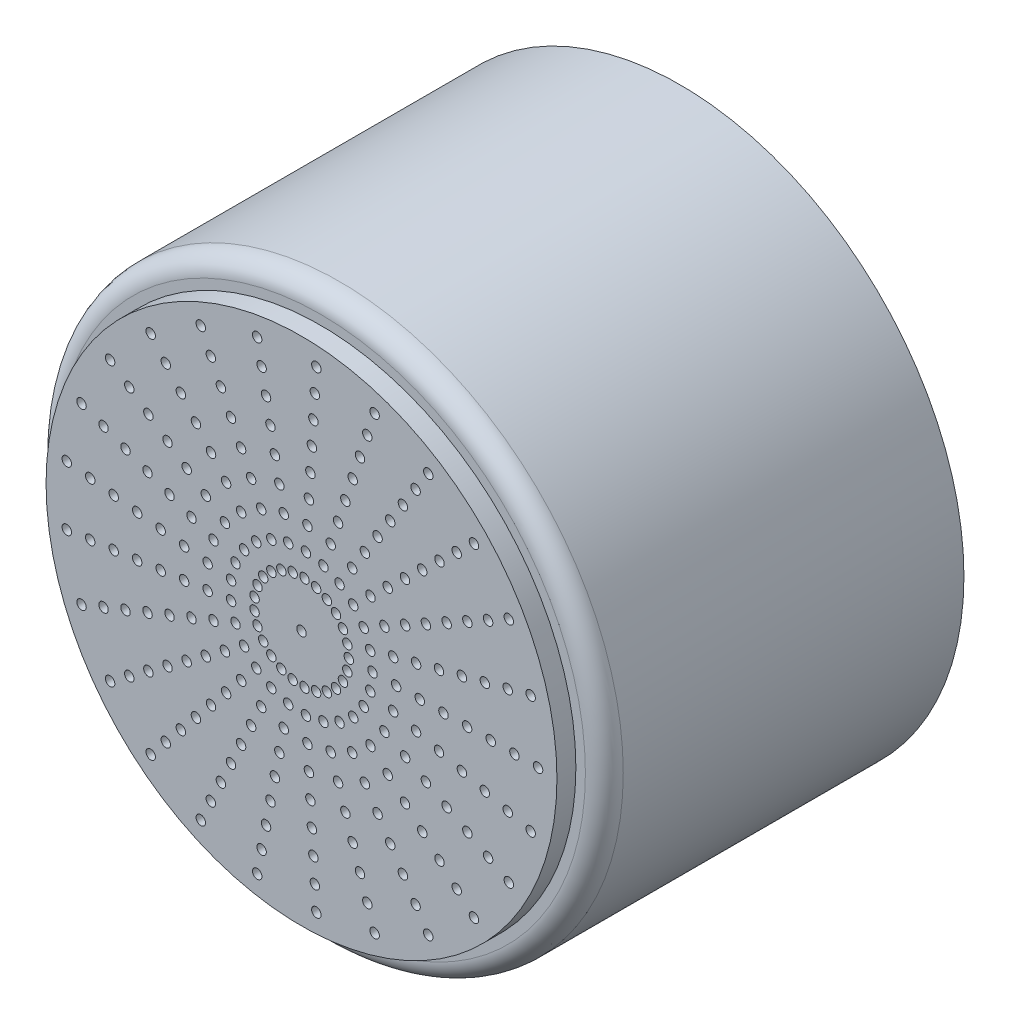
SolidWorks part; units mm, degrees
ref_plane "Ebene vorne" through (0, 0, 0) normal (0, 0, 1) x (1, 0, 0)
ref_plane "Ebene oben" through (0, 0, 0) normal (0, 1, 0) x (1, 0, 0)
ref_plane "Ebene rechts" through (0, 0, 0) normal (1, 0, 0) x (0, 0, -1)
sketch "Skizze1" plane through (0, 0, 0) normal (0, 0, 1) x (1, 0, 0)
  circle A0 centre (0, 0) radius 3
extrude "Aufsatz-Linear austragen1" add sketch "Skizze1" along normal blind 3.8
fillet "Verrundung1" radius 0.2 1 edges at (3, 0, 3.8)
sketch "Skizze2" plane through (0, 0, 3.8) normal (0, 0, 1) x (1, 0, 0)
  circle A0 centre (0, 0) radius 2.6993
extrude "Aufsatz-Linear austragen2" add sketch "Skizze2" along normal blind 0.2
sketch "Skizze3" plane through (0, 0, 4) normal (0, 0, 1) x (1, 0, 0)
  circle A0 centre (0, 0) radius 0.05
  circle A2 centre (0.5, 0) radius 0.05
  circle A3 centre (0.75, 0) radius 0.05
  circle A4 centre (1, 0) radius 0.05
  circle A5 centre (1.25, 0) radius 0.05
  circle A6 centre (1.5, 0) radius 0.05
  circle A7 centre (1.75, 0) radius 0.05
  circle A8 centre (2, 0) radius 0.05
  circle A9 centre (2.25, 0) radius 0.05
  circle A10 centre (2.5, 0) radius 0.05
  circle A11 centre (0, 0) radius 0.05
  circle A13 centre (0.4843, -0.1243) radius 0.05
  circle A14 centre (0.7264, -0.1865) radius 0.05
  circle A15 centre (0.9686, -0.2487) radius 0.05
  circle A16 centre (1.2107, -0.3109) radius 0.05
  circle A17 centre (1.4529, -0.373) radius 0.05
  circle A18 centre (1.695, -0.4352) radius 0.05
  circle A19 centre (1.9372, -0.4974) radius 0.05
  circle A20 centre (2.1793, -0.5596) radius 0.05
  circle A21 centre (2.4215, -0.6217) radius 0.05
  circle A22 centre (0, 0) radius 0.05
  circle A24 centre (0.4382, -0.2409) radius 0.05
  circle A25 centre (0.6572, -0.3613) radius 0.05
  circle A26 centre (0.8763, -0.4818) radius 0.05
  circle A27 centre (1.0954, -0.6022) radius 0.05
  circle A28 centre (1.3145, -0.7226) radius 0.05
  circle A29 centre (1.5335, -0.8431) radius 0.05
  circle A30 centre (1.7526, -0.9635) radius 0.05
  circle A31 centre (1.9717, -1.0839) radius 0.05
  circle A32 centre (2.1908, -1.2044) radius 0.05
  circle A33 centre (0, 0) radius 0.05
  circle A35 centre (0.3645, -0.3423) radius 0.05
  circle A36 centre (0.5467, -0.5134) radius 0.05
  circle A37 centre (0.729, -0.6845) radius 0.05
  circle A38 centre (0.9112, -0.8557) radius 0.05
  circle A39 centre (1.0935, -1.0268) radius 0.05
  circle A40 centre (1.2757, -1.198) radius 0.05
  circle A41 centre (1.4579, -1.3691) radius 0.05
  circle A42 centre (1.6402, -1.5402) radius 0.05
  circle A43 centre (1.8224, -1.7114) radius 0.05
  circle A44 centre (0, 0) radius 0.05
  circle A46 centre (0.2679, -0.4222) radius 0.05
  circle A47 centre (0.4019, -0.6332) radius 0.05
  circle A48 centre (0.5358, -0.8443) radius 0.05
  circle A49 centre (0.6698, -1.0554) radius 0.05
  circle A50 centre (0.8037, -1.2665) radius 0.05
  circle A51 centre (0.9377, -1.4776) radius 0.05
  circle A52 centre (1.0717, -1.6887) radius 0.05
  circle A53 centre (1.2056, -1.8997) radius 0.05
  circle A54 centre (1.3396, -2.1108) radius 0.05
  circle A55 centre (0, 0) radius 0.05
  circle A57 centre (0.1545, -0.4755) radius 0.05
  circle A58 centre (0.2318, -0.7133) radius 0.05
  circle A59 centre (0.309, -0.9511) radius 0.05
  circle A60 centre (0.3863, -1.1888) radius 0.05
  circle A61 centre (0.4635, -1.4266) radius 0.05
  circle A62 centre (0.5408, -1.6643) radius 0.05
  circle A63 centre (0.618, -1.9021) radius 0.05
  circle A64 centre (0.6953, -2.1399) radius 0.05
  circle A65 centre (0.7725, -2.3776) radius 0.05
  circle A66 centre (0, 0) radius 0.05
  circle A68 centre (0.0314, -0.499) radius 0.05
  circle A69 centre (0.0471, -0.7485) radius 0.05
  circle A70 centre (0.0628, -0.998) radius 0.05
  circle A71 centre (0.0785, -1.2475) radius 0.05
  circle A72 centre (0.0942, -1.497) radius 0.05
  circle A73 centre (0.1099, -1.7465) radius 0.05
  circle A74 centre (0.1256, -1.9961) radius 0.05
  circle A75 centre (0.1413, -2.2456) radius 0.05
  circle A76 centre (0.157, -2.4951) radius 0.05
  circle A77 centre (0, 0) radius 0.05
  circle A79 centre (-0.0937, -0.4911) radius 0.05
  circle A80 centre (-0.1405, -0.7367) radius 0.05
  circle A81 centre (-0.1874, -0.9823) radius 0.05
  circle A82 centre (-0.2342, -1.2279) radius 0.05
  circle A83 centre (-0.2811, -1.4734) radius 0.05
  circle A84 centre (-0.3279, -1.719) radius 0.05
  circle A85 centre (-0.3748, -1.9646) radius 0.05
  circle A86 centre (-0.4216, -2.2101) radius 0.05
  circle A87 centre (-0.4685, -2.4557) radius 0.05
  circle A88 centre (0, 0) radius 0.05
  circle A90 centre (-0.2129, -0.4524) radius 0.05
  circle A91 centre (-0.3193, -0.6786) radius 0.05
  circle A92 centre (-0.4258, -0.9048) radius 0.05
  circle A93 centre (-0.5322, -1.131) radius 0.05
  circle A94 centre (-0.6387, -1.3572) radius 0.05
  circle A95 centre (-0.7451, -1.5834) radius 0.05
  circle A96 centre (-0.8516, -1.8097) radius 0.05
  circle A97 centre (-0.958, -2.0359) radius 0.05
  circle A98 centre (-1.0644, -2.2621) radius 0.05
  circle A99 centre (0, 0) radius 0.05
  circle A101 centre (-0.3187, -0.3853) radius 0.05
  circle A102 centre (-0.4781, -0.5779) radius 0.05
  circle A103 centre (-0.6374, -0.7705) radius 0.05
  circle A104 centre (-0.7968, -0.9631) radius 0.05
  circle A105 centre (-0.9561, -1.1558) radius 0.05
  circle A106 centre (-1.1155, -1.3484) radius 0.05
  circle A107 centre (-1.2748, -1.541) radius 0.05
  circle A108 centre (-1.4342, -1.7337) radius 0.05
  circle A109 centre (-1.5936, -1.9263) radius 0.05
  circle A110 centre (0, 0) radius 0.05
  circle A112 centre (-0.4045, -0.2939) radius 0.05
  circle A113 centre (-0.6068, -0.4408) radius 0.05
  circle A114 centre (-0.809, -0.5878) radius 0.05
  circle A115 centre (-1.0113, -0.7347) radius 0.05
  circle A116 centre (-1.2135, -0.8817) radius 0.05
  circle A117 centre (-1.4158, -1.0286) radius 0.05
  circle A118 centre (-1.618, -1.1756) radius 0.05
  circle A119 centre (-1.8203, -1.3225) radius 0.05
  circle A120 centre (-2.0225, -1.4695) radius 0.05
  circle A121 centre (0, 0) radius 0.05
  circle A123 centre (-0.4649, -0.1841) radius 0.05
  circle A124 centre (-0.6973, -0.2761) radius 0.05
  circle A125 centre (-0.9298, -0.3681) radius 0.05
  circle A126 centre (-1.1622, -0.4602) radius 0.05
  circle A127 centre (-1.3947, -0.5522) radius 0.05
  circle A128 centre (-1.6271, -0.6442) radius 0.05
  circle A129 centre (-1.8596, -0.7362) radius 0.05
  circle A130 centre (-2.092, -0.8283) radius 0.05
  circle A131 centre (-2.3244, -0.9203) radius 0.05
  circle A132 centre (0, 0) radius 0.05
  circle A134 centre (-0.4961, -0.0627) radius 0.05
  circle A135 centre (-0.7441, -0.094) radius 0.05
  circle A136 centre (-0.9921, -0.1253) radius 0.05
  circle A137 centre (-1.2401, -0.1567) radius 0.05
  circle A138 centre (-1.4882, -0.188) radius 0.05
  circle A139 centre (-1.7362, -0.2193) radius 0.05
  circle A140 centre (-1.9842, -0.2507) radius 0.05
  circle A141 centre (-2.2323, -0.282) radius 0.05
  circle A142 centre (-2.4803, -0.3133) radius 0.05
  circle A143 centre (0, 0) radius 0.05
  circle A145 centre (-0.4961, 0.0627) radius 0.05
  circle A146 centre (-0.7441, 0.094) radius 0.05
  circle A147 centre (-0.9921, 0.1253) radius 0.05
  circle A148 centre (-1.2401, 0.1567) radius 0.05
  circle A149 centre (-1.4882, 0.188) radius 0.05
  circle A150 centre (-1.7362, 0.2193) radius 0.05
  circle A151 centre (-1.9842, 0.2507) radius 0.05
  circle A152 centre (-2.2323, 0.282) radius 0.05
  circle A153 centre (-2.4803, 0.3133) radius 0.05
  circle A154 centre (0, 0) radius 0.05
  circle A156 centre (-0.4649, 0.1841) radius 0.05
  circle A157 centre (-0.6973, 0.2761) radius 0.05
  circle A158 centre (-0.9298, 0.3681) radius 0.05
  circle A159 centre (-1.1622, 0.4602) radius 0.05
  circle A160 centre (-1.3947, 0.5522) radius 0.05
  circle A161 centre (-1.6271, 0.6442) radius 0.05
  circle A162 centre (-1.8596, 0.7362) radius 0.05
  circle A163 centre (-2.092, 0.8283) radius 0.05
  circle A164 centre (-2.3244, 0.9203) radius 0.05
  circle A165 centre (0, 0) radius 0.05
  circle A167 centre (-0.4045, 0.2939) radius 0.05
  circle A168 centre (-0.6068, 0.4408) radius 0.05
  circle A169 centre (-0.809, 0.5878) radius 0.05
  circle A170 centre (-1.0113, 0.7347) radius 0.05
  circle A171 centre (-1.2135, 0.8817) radius 0.05
  circle A172 centre (-1.4158, 1.0286) radius 0.05
  circle A173 centre (-1.618, 1.1756) radius 0.05
  circle A174 centre (-1.8203, 1.3225) radius 0.05
  circle A175 centre (-2.0225, 1.4695) radius 0.05
  circle A176 centre (0, 0) radius 0.05
  circle A178 centre (-0.3187, 0.3853) radius 0.05
  circle A179 centre (-0.4781, 0.5779) radius 0.05
  circle A180 centre (-0.6374, 0.7705) radius 0.05
  circle A181 centre (-0.7968, 0.9631) radius 0.05
  circle A182 centre (-0.9561, 1.1558) radius 0.05
  circle A183 centre (-1.1155, 1.3484) radius 0.05
  circle A184 centre (-1.2748, 1.541) radius 0.05
  circle A185 centre (-1.4342, 1.7337) radius 0.05
  circle A186 centre (-1.5936, 1.9263) radius 0.05
  circle A187 centre (0, 0) radius 0.05
  circle A189 centre (-0.2129, 0.4524) radius 0.05
  circle A190 centre (-0.3193, 0.6786) radius 0.05
  circle A191 centre (-0.4258, 0.9048) radius 0.05
  circle A192 centre (-0.5322, 1.131) radius 0.05
  circle A193 centre (-0.6387, 1.3572) radius 0.05
  circle A194 centre (-0.7451, 1.5834) radius 0.05
  circle A195 centre (-0.8516, 1.8097) radius 0.05
  circle A196 centre (-0.958, 2.0359) radius 0.05
  circle A197 centre (-1.0644, 2.2621) radius 0.05
  circle A198 centre (0, 0) radius 0.05
  circle A200 centre (-0.0937, 0.4911) radius 0.05
  circle A201 centre (-0.1405, 0.7367) radius 0.05
  circle A202 centre (-0.1874, 0.9823) radius 0.05
  circle A203 centre (-0.2342, 1.2279) radius 0.05
  circle A204 centre (-0.2811, 1.4734) radius 0.05
  circle A205 centre (-0.3279, 1.719) radius 0.05
  circle A206 centre (-0.3748, 1.9646) radius 0.05
  circle A207 centre (-0.4216, 2.2101) radius 0.05
  circle A208 centre (-0.4685, 2.4557) radius 0.05
  circle A209 centre (0, 0) radius 0.05
  circle A211 centre (0.0314, 0.499) radius 0.05
  circle A212 centre (0.0471, 0.7485) radius 0.05
  circle A213 centre (0.0628, 0.998) radius 0.05
  circle A214 centre (0.0785, 1.2475) radius 0.05
  circle A215 centre (0.0942, 1.497) radius 0.05
  circle A216 centre (0.1099, 1.7465) radius 0.05
  circle A217 centre (0.1256, 1.9961) radius 0.05
  circle A218 centre (0.1413, 2.2456) radius 0.05
  circle A219 centre (0.157, 2.4951) radius 0.05
  circle A220 centre (0, 0) radius 0.05
  circle A222 centre (0.1545, 0.4755) radius 0.05
  circle A223 centre (0.2318, 0.7133) radius 0.05
  circle A224 centre (0.309, 0.9511) radius 0.05
  circle A225 centre (0.3863, 1.1888) radius 0.05
  circle A226 centre (0.4635, 1.4266) radius 0.05
  circle A227 centre (0.5408, 1.6643) radius 0.05
  circle A228 centre (0.618, 1.9021) radius 0.05
  circle A229 centre (0.6953, 2.1399) radius 0.05
  circle A230 centre (0.7725, 2.3776) radius 0.05
  circle A231 centre (0, 0) radius 0.05
  circle A233 centre (0.2679, 0.4222) radius 0.05
  circle A234 centre (0.4019, 0.6332) radius 0.05
  circle A235 centre (0.5358, 0.8443) radius 0.05
  circle A236 centre (0.6698, 1.0554) radius 0.05
  circle A237 centre (0.8037, 1.2665) radius 0.05
  circle A238 centre (0.9377, 1.4776) radius 0.05
  circle A239 centre (1.0717, 1.6887) radius 0.05
  circle A240 centre (1.2056, 1.8997) radius 0.05
  circle A241 centre (1.3396, 2.1108) radius 0.05
  circle A242 centre (0, 0) radius 0.05
  circle A244 centre (0.3645, 0.3423) radius 0.05
  circle A245 centre (0.5467, 0.5134) radius 0.05
  circle A246 centre (0.729, 0.6845) radius 0.05
  circle A247 centre (0.9112, 0.8557) radius 0.05
  circle A248 centre (1.0935, 1.0268) radius 0.05
  circle A249 centre (1.2757, 1.198) radius 0.05
  circle A250 centre (1.4579, 1.3691) radius 0.05
  circle A251 centre (1.6402, 1.5402) radius 0.05
  circle A252 centre (1.8224, 1.7114) radius 0.05
  circle A253 centre (0, 0) radius 0.05
  circle A255 centre (0.4382, 0.2409) radius 0.05
  circle A256 centre (0.6572, 0.3613) radius 0.05
  circle A257 centre (0.8763, 0.4818) radius 0.05
  circle A258 centre (1.0954, 0.6022) radius 0.05
  circle A259 centre (1.3145, 0.7226) radius 0.05
  circle A260 centre (1.5335, 0.8431) radius 0.05
  circle A261 centre (1.7526, 0.9635) radius 0.05
  circle A262 centre (1.9717, 1.0839) radius 0.05
  circle A263 centre (2.1908, 1.2044) radius 0.05
  circle A264 centre (0, 0) radius 0.05
  circle A266 centre (0.4843, 0.1243) radius 0.05
  circle A267 centre (0.7264, 0.1865) radius 0.05
  circle A268 centre (0.9686, 0.2487) radius 0.05
  circle A269 centre (1.2107, 0.3109) radius 0.05
  circle A270 centre (1.4529, 0.373) radius 0.05
  circle A271 centre (1.695, 0.4352) radius 0.05
  circle A272 centre (1.9372, 0.4974) radius 0.05
  circle A273 centre (2.1793, 0.5596) radius 0.05
  circle A274 centre (2.4215, 0.6217) radius 0.05
  circle A281 centre (0.25, 0) radius 0.05 [skipped]
  point P529 (0, 0)
  dimension "D1" = 11
  dimension "D2" = 25
extrude "Schnitt-Linear austragen1" cut sketch "Skizze3" against normal blind 3
